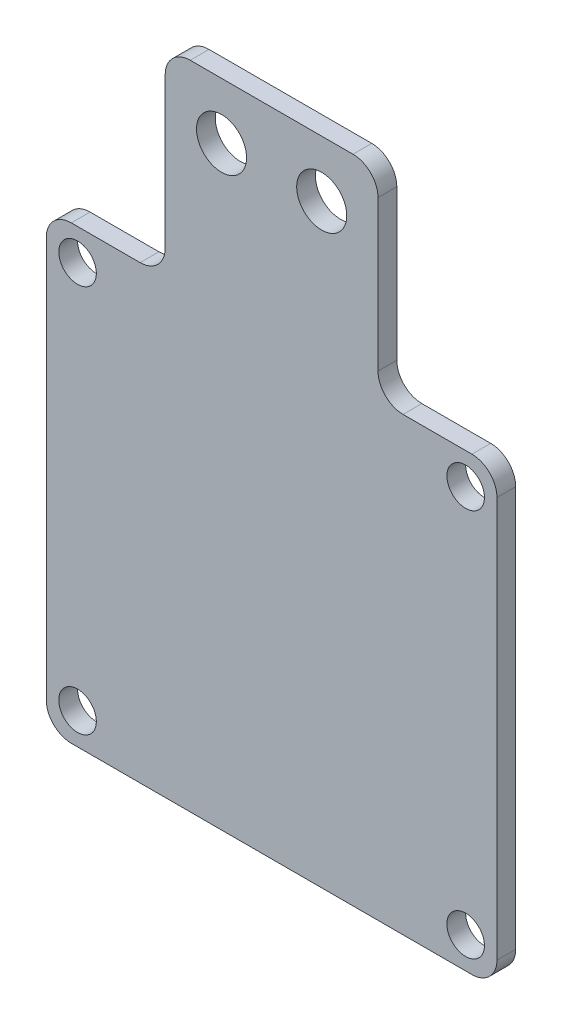
SolidWorks part; units mm, degrees
ref_plane "Alzado" through (0, 0, 0) normal (0, 0, 1) x (1, 0, 0)
ref_plane "Planta" through (0, 0, 0) normal (0, 1, 0) x (1, 0, 0)
ref_plane "Vista lateral" through (0, 0, 0) normal (1, 0, 0) x (0, 0, -1)
sketch "Croquis1" plane through (0, 0, 0) normal (0, 0, 1) x (1, 0, 0)
  line L0 (0, 0) -> (0, 52) construction
  line L1 (0, 0) -> (-16, 0)
  line L2 (-18, 2) -> (-18, 34)
  line L3 (-16, 36) -> (-10.5, 36)
  line L4 (-8.5, 38) -> (-8.5, 50)
  line L5 (-6.5, 52) -> (0, 52)
  line L6 (-1, 1) -> (-16, 1) construction
  line L7 (-17, 2) -> (-17, 34) construction
  line L8 (-16, 35) -> (-10.5, 35) construction
  line L12 (-6.5, 51) -> (-1, 51) construction
  line L13 (-7.5, 38) -> (-7.5, 50) construction
  line L14 (-1, 1) -> (-1, 51) construction
  line L15 (-8.5, 49.5) -> (-6, 49.5) construction
  line L16 (-6, 49.5) -> (-6, 52) construction
  line L17 (-6, 49.5) -> (-0.2181, 49.5) construction
  line L18 (-6, 49.5) -> (-6, 42.8951) construction
  line L19 (6, 49.5) -> (6, 42.8951) construction
  line L20 (6, 49.5) -> (0.2181, 49.5) construction
  line L21 (6, 49.5) -> (6, 52) construction
  line L22 (8.5, 49.5) -> (6, 49.5) construction
  line L23 (16, 35) -> (10.5, 35) construction
  line L24 (17, 2) -> (17, 34) construction
  line L25 (1, 1) -> (16, 1) construction
  line L26 (6.5, 52) -> (0, 52)
  line L27 (8.5, 38) -> (8.5, 50)
  line L28 (16, 36) -> (10.5, 36)
  line L29 (18, 2) -> (18, 34)
  line L30 (0, 0) -> (16, 0)
  arc A0 (-8.5, 50) -> (-6.5, 52) centre (-6.5, 50) cw
  arc A1 (-8.5, 38) -> (-10.5, 36) centre (-10.5, 38) cw
  arc A2 (-18, 34) -> (-16, 36) centre (-16, 34) cw
  arc A3 (-16, 0) -> (-18, 2) centre (-16, 2) cw
  arc A4 (-16, 1) -> (-17, 2) centre (-16, 2) cw construction
  arc A5 (-17, 34) -> (-16, 35) centre (-16, 34) cw construction
  circle A8 centre (-15.5, 2.5) radius 1.5
  circle A9 centre (-15.5, 33.5) radius 1.5
  arc A10 (-7.5, 38) -> (-10.5, 35) centre (-10.5, 38) cw construction
  arc A11 (-7.5, 50) -> (-6.5, 51) centre (-6.5, 50) cw construction
  circle A12 centre (-4, 47.5) radius 2
  arc A13 (17, 34) -> (16, 35) centre (16, 34) ccw construction
  arc A14 (16, 1) -> (17, 2) centre (16, 2) ccw construction
  circle A15 centre (4, 47.5) radius 2
  circle A16 centre (15.5, 33.5) radius 1.5
  circle A17 centre (15.5, 2.5) radius 1.5
  arc A18 (16, 0) -> (18, 2) centre (16, 2) ccw
  arc A19 (18, 34) -> (16, 36) centre (16, 34) ccw
  arc A20 (8.5, 38) -> (10.5, 36) centre (10.5, 38) ccw
  arc A21 (8.5, 50) -> (6.5, 52) centre (6.5, 50) ccw
  point P0 (6, 47.5)
  point P33 (-17, 2.5)
  point P34 (-15.5, 1)
  point P35 (-15.5, 35)
  point P36 (-17, 33.5)
  point P44 (-4, 49.5)
  point P45 (-6, 47.5)
  point P68 (4, 49.5)
  point P81 (17, 33.5)
  point P82 (15.5, 35)
  point P83 (15.5, 1)
  point P84 (17, 2.5)
  dimension "D5" = 2
  dimension "D7" = 2.5
  dimension "D8" = 3
  dimension "D10" = 4
  dimension "D1" = 52
  dimension "D2" = 36
  dimension "D3" = 17
  dimension "D4" = 36
  dimension "D9" = 2.5
  dimension "D6" = 1
extrude "Saliente-Extruir1" add sketch "Croquis1" along normal blind 1.5
